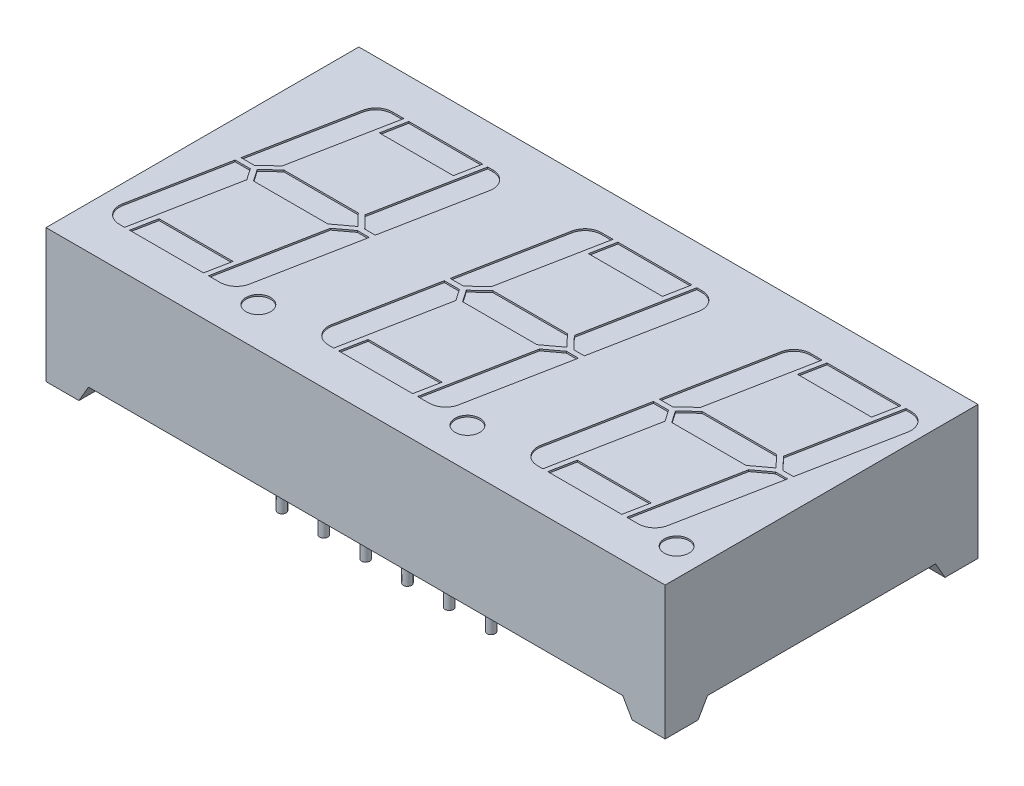
SolidWorks part; units mm, degrees
ref_plane "Спереди" through (0, 0, 0) normal (0, 0, 1) x (1, 0, 0)
ref_plane "Сверху" through (0, 0, 0) normal (0, 1, 0) x (1, 0, 0)
ref_plane "Справа" through (0, 0, 0) normal (1, 0, 0) x (0, 0, -1)
sketch "Эскиз1" plane through (0, 0, 0) normal (0, 1, 0) x (1, 0, 0)
  line L1 (-18.8, 9.5) -> (18.8, 9.5)
  line L2 (-18.8, 9.5) -> (-18.8, -9.5)
  line L3 (-18.8, -9.5) -> (18.8, -9.5)
  line L4 (18.8, 9.5) -> (18.8, -9.5)
  line L5 (-18.8, 9.5) -> (18.8, -9.5) construction
  line L6 (-18.8, -9.5) -> (18.8, 9.5) construction
  point P0 (0, 0)
  dimension "D1" = 37.6
  dimension "D2" = 19
extrude "Бобышка-Вытянуть1" add sketch "Эскиз1" along normal blind 8.1
sketch "Эскиз2" plane through (0, 8.1, 0) normal (0, 1, 0) x (1, 0, 0)
  line L0 (-18.8, 0) -> (18.8, 0) construction
  line L1 (-18.8, 9.5) -> (-18.8, -9.5) construction
  line L2 (18.8, -9.5) -> (18.8, 9.5) construction
  line L3 (-15.1948, 7.1) -> (-17.9549, -7.1)
  line L4 (-17.9549, -7.1) -> (-9.8052, -7.1)
  line L5 (-9.8052, -7.1) -> (-7.0451, 7.1)
  line L6 (-7.0451, 7.1) -> (-15.1948, 7.1)
  line L7 (-15.1948, 7.1) -> (-9.8052, -7.1) construction
  line L8 (-17.9549, -7.1) -> (-7.0451, 7.1) construction
  line L9 (-13.9583, 5.6) -> (-16.1353, -5.6)
  line L10 (-16.1353, -5.6) -> (-11.0417, -5.6)
  line L11 (-11.0417, -5.6) -> (-8.8647, 5.6)
  line L12 (-8.8647, 5.6) -> (-13.9583, 5.6)
  line L13 (-16.4291, 0.75) -> (-8.2794, 0.75)
  line L14 (-5.4306, 7.6882) -> (-8.8177, -9.7378) construction
  line L15 (-16.7206, -0.75) -> (-8.5709, -0.75)
  line L16 (-2.4948, 7.1) -> (-5.2549, -7.1)
  line L17 (-5.2549, -7.1) -> (2.8948, -7.1)
  line L18 (2.8948, -7.1) -> (5.6549, 7.1)
  line L19 (5.6549, 7.1) -> (-2.4948, 7.1)
  line L20 (-1.2583, 5.6) -> (-3.4353, -5.6)
  line L21 (-3.4353, -5.6) -> (1.6583, -5.6)
  line L22 (1.6583, -5.6) -> (3.8353, 5.6)
  line L23 (3.8353, 5.6) -> (-1.2583, 5.6)
  line L24 (-3.7291, 0.75) -> (4.4206, 0.75)
  line L25 (-4.0206, -0.75) -> (4.1291, -0.75)
  line L26 (-2.4948, 7.1) -> (2.8948, -7.1) construction
  line L27 (-5.2549, -7.1) -> (5.6549, 7.1) construction
  line L53 (-8.4251, 0) -> (-3.8749, 0)
  line L54 (-9.8052, -7.1) -> (-5.2549, -7.1) construction
  line L55 (1.6079, 8.2724) -> (-1.6079, -8.2724) construction
  line L56 (10.2052, 7.1) -> (7.4451, -7.1)
  line L57 (7.4451, -7.1) -> (15.5948, -7.1)
  line L58 (15.5948, -7.1) -> (18.3549, 7.1)
  line L59 (18.3549, 7.1) -> (10.2052, 7.1)
  line L60 (11.4417, 5.6) -> (9.2647, -5.6)
  line L61 (9.2647, -5.6) -> (14.3583, -5.6)
  line L62 (14.3583, -5.6) -> (16.5353, 5.6)
  line L63 (16.5353, 5.6) -> (11.4417, 5.6)
  line L64 (8.9709, 0.75) -> (17.1206, 0.75)
  line L65 (8.6794, -0.75) -> (16.8291, -0.75)
  line L66 (22.9052, 7.1) -> (20.1451, -7.1)
  line L67 (20.1451, -7.1) -> (28.2948, -7.1)
  line L68 (28.2948, -7.1) -> (31.0549, 7.1)
  line L69 (31.0549, 7.1) -> (22.9052, 7.1)
  line L70 (24.1417, 5.6) -> (21.9647, -5.6)
  line L71 (21.9647, -5.6) -> (27.0583, -5.6)
  line L72 (27.0583, -5.6) -> (29.2353, 5.6)
  line L73 (29.2353, 5.6) -> (24.1417, 5.6)
  line L74 (21.6709, 0.75) -> (29.8206, 0.75)
  line L75 (21.3794, -0.75) -> (29.5291, -0.75)
  line L76 (10.2052, 7.1) -> (15.5948, -7.1) construction
  line L77 (7.4451, -7.1) -> (18.3549, 7.1) construction
  line L78 (22.9052, 7.1) -> (28.2948, -7.1) construction
  line L79 (20.1451, -7.1) -> (31.0549, 7.1) construction
  point P8 (-8.4251, 0)
  point P11 (-12.5, 0)
  point P21 (0, 0)
  point P29 (0.2, 0)
  point P38 (25.6, 0)
  point P39 (12.9, 0)
  dimension "D1" = 14.2
  dimension "D2" = 8
  dimension "D4" = 1.5
  dimension "D5" = 12.5
  dimension "D7" = 12.7
  dimension "D3" = 1.5
  dimension "D6" = 4
sketch "Эскиз3" plane through (0, 8.1, 0) normal (0, 1, 0) x (1, 0, 0)
  line L6 (-8.4251, 0) -> (-9.0879, 0) construction
  line L7 (-9.0879, 0) -> (-9.8074, 0.75) construction
  line L8 (-10.099, -0.75) -> (-9.0879, 0) construction
  line L9 (-9.8052, -7.1) -> (-7.0451, 7.1) construction
  line L10 (-16.6137, -0.2) -> (-15.694, -0.2)
  line L11 (-15.4476, -0.0289) -> (-14.6067, 0.75)
  line L12 (-11.0417, -5.6) -> (-8.8647, 5.6) construction
  line L13 (-14.9495, -0.75) -> (-15.4476, -0.0289)
  line L14 (-13.9583, 5.6) -> (-16.1353, -5.6) construction
  line L15 (-7.0451, 7.1) -> (-15.1948, 7.1) construction
  line L16 (-13.6583, 5.6) -> (-13.3668, 7.1)
  line L17 (-13.6583, 5.6) -> (-9.1647, 5.6)
  line L18 (-13.3668, 7.1) -> (-8.8732, 7.1)
  line L19 (-9.1647, 5.6) -> (-8.8732, 7.1)
  line L20 (-8.8647, 5.6) -> (-13.9583, 5.6) construction
  line L21 (-16.1268, -7.1) -> (-15.8353, -5.6)
  line L22 (-16.1268, -7.1) -> (-11.6332, -7.1)
  line L23 (-15.8353, -5.6) -> (-11.3417, -5.6)
  line L24 (-11.6332, -7.1) -> (-11.3417, -5.6)
  line L25 (-17.9549, -7.1) -> (-9.8052, -7.1) construction
  line L26 (-16.1353, -5.6) -> (-11.0417, -5.6) construction
  line L27 (-16.5749, 0) -> (-15.7106, 0) construction
  line L28 (-15.1948, 7.1) -> (-17.9549, -7.1) construction
  line L29 (-18.8, 0) -> (18.8, 0) construction
  line L30 (-15.7106, 0) -> (-14.901, 0.75) construction
  line L33 (-16.7206, -0.75) -> (-8.5709, -0.75) construction
  line L34 (-15.1926, -0.75) -> (-15.7106, 0) construction
  line L35 (-16.4291, 0.75) -> (-8.2794, 0.75) construction
  line L36 (-8.4057, 0.1) -> (-9.0452, 0.1)
  line L37 (-8.464, -0.2) -> (-9.0879, -0.2)
  line L38 (-9.0452, 0.1) -> (-9.7841, 0.8701)
  line L39 (-16.5554, 0.1) -> (-15.7498, 0.1)
  line L40 (-15.7498, 0.1) -> (-14.969, 0.8234)
  line L41 (-15.2193, -0.8873) -> (-15.694, -0.2)
  line L42 (-9.3894, 0.0254) -> (-9.9518, 0.6115)
  line L43 (-10.1273, -0.8955) -> (-9.1896, -0.2)
  line L44 (-10.4347, -0.75) -> (-9.3894, 0.0254)
  line L45 (-16.5749, -0.2) -> (-15.7106, -0.2) construction
  line L46 (-15.2748, -0.8068) -> (-15.7929, -0.0568) construction
  line L47 (-16.5749, 0.1) -> (-15.7106, 0.1) construction
  line L48 (-15.7786, 0.0734) -> (-14.969, 0.8234) construction
  line L49 (-15.5747, -0.1467) -> (-14.7651, 0.6033) construction
  line L50 (-15.028, -0.6363) -> (-15.5461, 0.1137) construction
  line L51 (-14.969, 0.8234) -> (-14.8687, 0.9162)
  line L52 (-10.0394, -0.8303) -> (-9.0283, -0.0803) construction
  line L53 (-10.2181, -0.5894) -> (-9.207, 0.1606) construction
  line L54 (-9.2322, -0.1385) -> (-9.9518, 0.6115) construction
  line L55 (-9.0157, 0.0692) -> (-9.7353, 0.8192) construction
  line L56 (-8.4251, 0.1) -> (-9.0879, 0.1) construction
  line L57 (-8.4251, -0.2) -> (-9.0879, -0.2) construction
  line L58 (-9.0879, -0.2) -> (-9.1896, -0.2)
  line L59 (-9.9518, 0.6115) -> (-10.0846, 0.75)
  line L60 (-9.7841, 0.8701) -> (-8.5732, 7.1)
  line L61 (-8.5732, 7.1) -> (-8.2582, 7.1)
  line L62 (-7.2766, 5.9092) -> (-8.4057, 0.1)
  line L63 (-10.1273, -0.8955) -> (-11.3332, -7.1)
  line L64 (-11.3332, -7.1) -> (-10.6295, -7.1)
  line L65 (-9.6479, -6.2908) -> (-8.464, -0.2)
  line L66 (-16.6137, -0.2) -> (-17.7234, -5.9092)
  line L67 (-16.7418, -7.1) -> (-16.4268, -7.1)
  line L68 (-16.4268, -7.1) -> (-15.2193, -0.8873)
  line L69 (-15.3521, 6.2908) -> (-16.5554, 0.1)
  line L70 (-14.3705, 7.1) -> (-13.6668, 7.1)
  line L71 (-13.6668, 7.1) -> (-14.8687, 0.9162)
  line L72 (-14.6067, 0.75) -> (-10.0846, 0.75)
  line L73 (-14.9495, -0.75) -> (-10.4347, -0.75)
  line L76 (-9.8052, -7.1) -> (-5.2549, -7.1) construction
  line L77 (-5.4306, 7.6882) -> (-8.8177, -9.7378) construction
  arc A0 (-8.2582, 7.1) -> (-7.2766, 5.9092) centre (-8.2582, 6.1) cw
  arc A1 (-10.6295, -7.1) -> (-9.6479, -6.2908) centre (-10.6295, -6.1) ccw
  arc A2 (-17.7234, -5.9092) -> (-16.7418, -7.1) centre (-16.7418, -6.1) ccw
  arc A3 (-15.3521, 6.2908) -> (-14.3705, 7.1) centre (-14.3705, 6.1) cw
  circle A4 centre (-8.305, -7.1) radius 0.75
  point P69 (-7.0451, 7.1)
  point P87 (-9.8052, -7.1)
  point P90 (-17.9549, -7.1)
  point P96 (-15.1948, 7.1)
  dimension "D11" = 1
  dimension "D12" = 1
  dimension "D13" = 0.6627
  dimension "D1" = 0.3
  dimension "D2" = 0.3
  dimension "D3" = 0.2
  dimension "D5" = 0.1
  dimension "D14" = 0.8642
  dimension "D15" = 1.5
  dimension "D4" = 0.1
  dimension "D6" = 0.2
  dimension "D7" = 0.1
  dimension "D8" = 0.2
  dimension "D9" = 0.1
  dimension "D10" = 0.2
extrude "Вырез-Вытянуть1" cut sketch "Эскиз3" against normal blind 0.1
pattern_linear "Линейный массив1" count 3 spacing 12.7 along (1, 0, 0) of "Вырез-Вытянуть1"
sketch "Эскиз5" plane through (0, 0, 9.5) normal (0, 0, 1) x (1, 0, 0)
  line L0 (-16.8, 0) -> (-16.2226, 1)
  line L1 (-18.8, 0) -> (18.8, 0) construction
  line L2 (-16.2226, 1) -> (16.2226, 1)
  line L3 (0, -5.215) -> (0, 11.9692) construction
  line L4 (-18.8, 8.1) -> (-18.8, 0) construction
  line L5 (16.8, 0) -> (16.2226, 1)
  line L6 (-16.8, 0) -> (16.8, 0)
  point P12 (0, 1)
  dimension "D1" = 1
  dimension "D2" = 2
  dimension "D3" = 60
extrude "Вырез-Вытянуть4" cut sketch "Эскиз5" against normal through all contours L6 L5 L2 L0
sketch "Эскиз6" plane through (18.8, 0, 0) normal (1, 0, 0) x (0, 0, -1)
  line L0 (-7.5, 0) -> (-6.9226, 1)
  line L1 (-9.5, 0) -> (9.5, 0) construction
  line L2 (-6.9226, 1) -> (6.9226, 1)
  line L3 (0, 1) -> (0, 0) construction
  line L4 (7.5, 0) -> (-7.5, 0)
  line L5 (7.5, 0) -> (6.9226, 1)
  line L6 (-9.5, 8.1) -> (-9.5, 0) construction
  dimension "D1" = 1
  dimension "D2" = 2
extrude "Вырез-Вытянуть5" cut sketch "Эскиз6" against normal through all
sketch "Эскиз7" plane through (0, 1, 0) normal (0, -1, 0) x (1, 0, 0)
  line L0 (0, -11.0905) -> (0, 11.6186) construction
  line L1 (21.4931, 7.62) -> (-20.0237, 7.62) construction
  line L2 (27.4361, 0) -> (-27.8163, 0) construction
  line L3 (21.3247, -7.62) -> (-19.4174, -7.62) construction
  circle A0 centre (-1.27, -7.62) radius 0.25
  circle A1 centre (-3.81, -7.62) radius 0.25
  circle A2 centre (-6.35, -7.62) radius 0.25
  circle A3 centre (6.35, -7.62) radius 0.25
  circle A4 centre (3.81, -7.62) radius 0.25
  circle A5 centre (1.27, -7.62) radius 0.25
  circle A6 centre (1.27, 7.62) radius 0.25
  circle A7 centre (3.81, 7.62) radius 0.25
  circle A8 centre (6.35, 7.62) radius 0.25
  circle A9 centre (-6.35, 7.62) radius 0.25
  circle A10 centre (-3.81, 7.62) radius 0.25
  circle A11 centre (-1.27, 7.62) radius 0.25
  dimension "D3" = 0.5
  dimension "D1" = 15.24
  dimension "D2" = 7.62
  dimension "D4" = 2.54
  dimension "D5" = 2.54
  dimension "D6" = 1.27
extrude "Бобышка-Вытянуть3" add sketch "Эскиз7" along normal blind 2.5 and the other way blind 1
equation "\"D2@Эскиз7\"=\"D1@Эскиз7\"/2"
equation "\"D5@Эскиз7\"=\"D4@Эскиз7\""
equation "\"D6@Эскиз7\"=\"D4@Эскиз7\"/2"
equation "\"2ю5\"=5"
